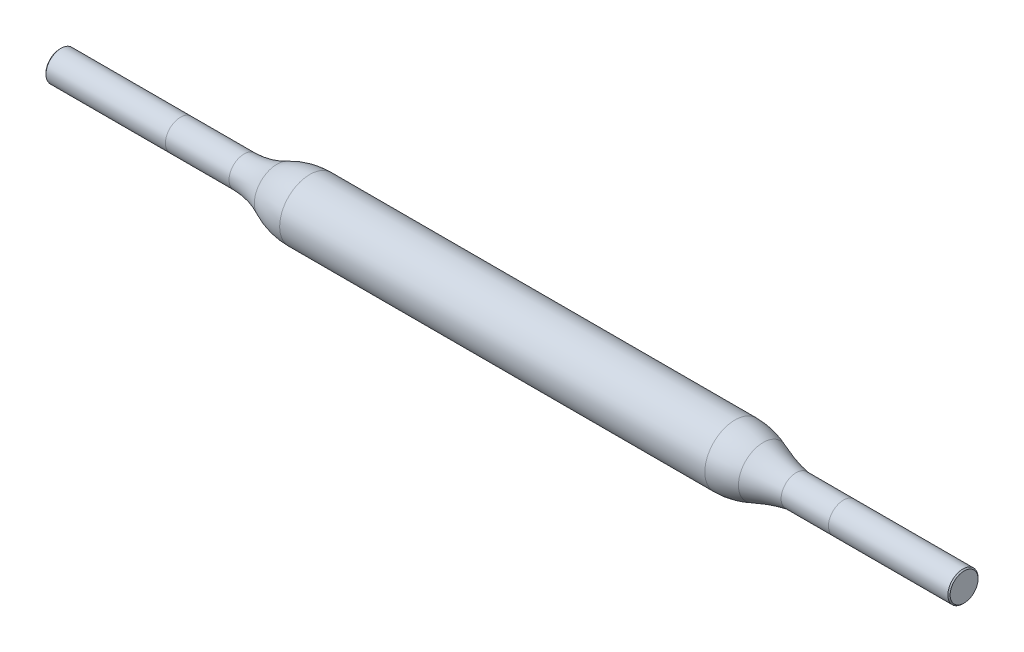
SolidWorks part; units mm, degrees
ref_plane "Front Plane" through (0, 0, 0) normal (0, 0, 1) x (1, 0, 0)
ref_plane "Top Plane" through (0, 0, 0) normal (0, 1, 0) x (1, 0, 0)
ref_plane "Right Plane" through (0, 0, 0) normal (1, 0, 0) x (0, 0, -1)
sketch "Sketch1" plane through (0, 0, 0) normal (0, 0, 1) x (1, 0, 0)
  line L0 (-31.1299, 0) -> (28.8701, 0)
  line L1 (28.8701, 0) -> (28.8701, 1)
  line L2 (-31.1299, 0) -> (-31.1299, 1)
  line L3 (-31.1299, 1) -> (-18.907, 1)
  line L4 (28.8701, 1) -> (17.7271, 1)
  line L5 (-14.5481, 2) -> (13.6659, 2)
  arc A0 (-18.907, 1) -> (-16.7276, 1.5) centre (-18.907, 6) ccw
  arc A1 (17.7271, 1) -> (15.5347, 1.6376) centre (19.8076, 12.2413) cw
  arc A2 (13.6659, 2) -> (15.5347, 1.6376) centre (13.6659, -3) cw
  arc A3 (-16.7276, 1.5) -> (-14.5481, 2) centre (-14.5481, -3) cw
  point P13 (14.7271, 2)
  point P16 (-15.907, 2)
  dimension "D5" = 3
  dimension "D7" = 5
  dimension "D1" = 60
  dimension "D2" = 1
  dimension "D3" = 1
  dimension "D4" = 2
  dimension "D6" = 3
revolve "Revolve1" add sketch "Sketch1" angle 360 about L0
sketch "Sketch2" plane through (0, 0, 0) normal (0, 0, 1) x (1, 0, 0)
  line L0 (-23.1299, 5.762) -> (-23.1299, -5.9412)
  line L1 (20.8701, 5.762) -> (20.8701, -6.6981)
  line L2 (-31.1299, 1) -> (-31.1299, -1) construction
  line L3 (28.8701, -1) -> (28.8701, 1) construction
  dimension "D1" = 8
  dimension "D2" = 8
split line "Split Line1"
chamfer "Chamfer1" distance 0.075 angle 45 2 edges at (28.8701, 0, 1) (-31.1299, 0, 1)
